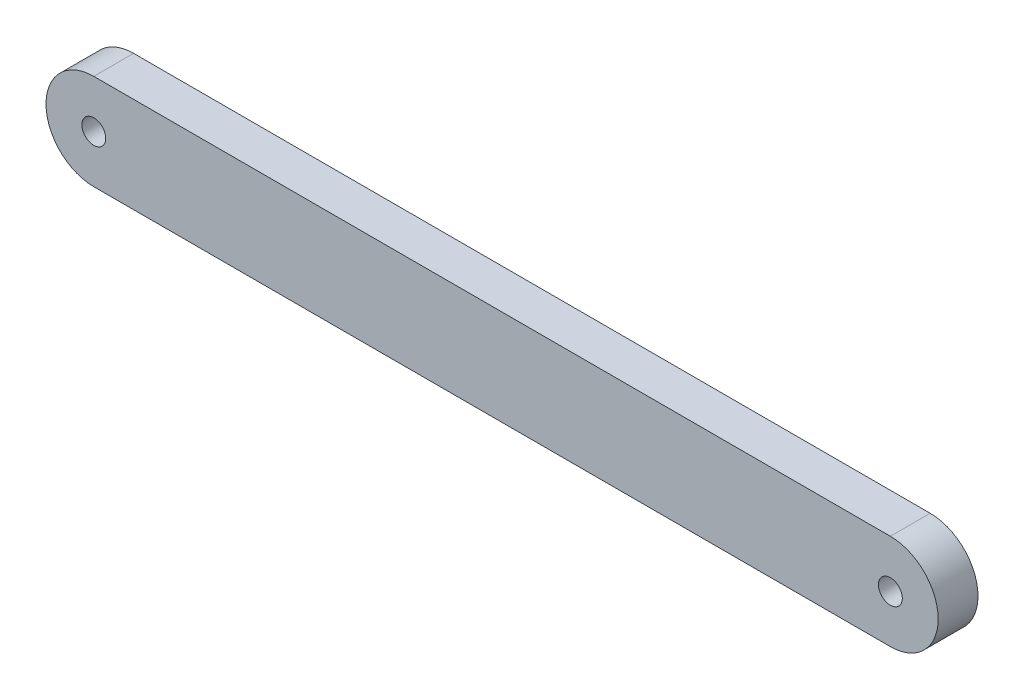
SolidWorks part; units mm, degrees
ref_plane "Plan de face" through (0, 0, 0) normal (0, 0, 1) x (1, 0, 0)
ref_plane "Plan de dessus" through (0, 0, 0) normal (0, 1, 0) x (1, 0, 0)
ref_plane "Plan de droite" through (0, 0, 0) normal (1, 0, 0) x (0, 0, -1)
sketch "Esquisse1" plane through (0, 0, 0) normal (0, 0, 1) x (1, 0, 0)
  line L0 (-50, 0) -> (50, 0) construction
  line L1 (-50, 6) -> (50, 6)
  line L2 (-50, -6) -> (50, -6)
  arc A0 (-50, 6) -> (-50, -6) centre (-50, 0) ccw
  arc A1 (50, -6) -> (50, 6) centre (50, 0) ccw
  circle A2 centre (-50, 0) radius 1.5
  circle A3 centre (50, 0) radius 1.5
  point P2 (0, 0)
  dimension "D1" = 6
  dimension "D3" = 3
  dimension "D4" = 3
  dimension "D2" = 100
extrude "Boss.-Extru.1" add sketch "Esquisse1" along normal blind 5
